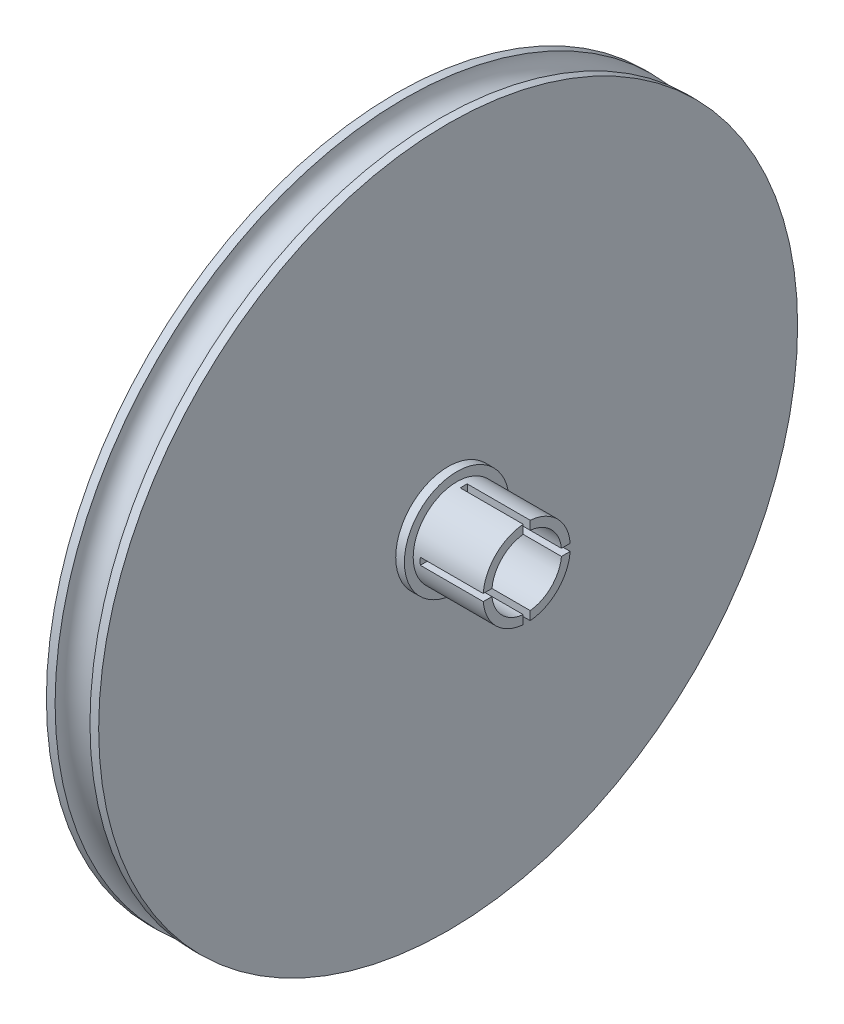
SolidWorks part; units mm, degrees
ref_plane "Front Plane" through (0, 0, 0) normal (0, 0, 1) x (1, 0, 0)
ref_plane "Top Plane" through (0, 0, 0) normal (0, 1, 0) x (1, 0, 0)
ref_plane "Right Plane" through (0, 0, 0) normal (1, 0, 0) x (0, 0, -1)
sketch "Sketch1" plane through (0, 0, 0) normal (0, 0, 1) x (1, 0, 0)
  line L0 (0, 0) -> (9.4996, 0) construction
  line L1 (0, 31.75) -> (0.7916, 31.75)
  line L2 (0, 31.75) -> (0, 3.1725)
  line L3 (0, 3.1725) -> (11.8872, 3.1725)
  line L4 (4.7498, 31.75) -> (4.7498, 4.7625)
  line L5 (3.9582, 31.75) -> (4.7498, 31.75)
  line L6 (0.7916, 31.75) -> (3.9582, 31.75) construction
  line L7 (0, 31.75) -> (4.7498, 31.75) construction
  line L8 (4.7498, 4.7625) -> (11.8872, 4.7625)
  line L9 (11.8872, 4.7625) -> (11.8872, 3.1725)
  circle A0 centre (2.3749, 31.75) radius 1.5833 construction
  arc A1 (0.7916, 31.75) -> (3.9582, 31.75) centre (2.3749, 31.75) ccw
  dimension "D2" = 3.1667
  dimension "Inside Diameter [A]" = 6.3449
  dimension "Outside Diameter [OD]" = 63.5
  dimension "D1" = 4.7498
  dimension "Diameter [E]" = 9.525
  dimension "D3" = 11.8872
revolve "Revolve1-MAIN BODY" add sketch "Sketch1" angle 360 about L0
sketch "Sketch2" plane through (0, 0, 0) normal (0, 0, 1) x (1, 0, 0)
  line L0 (0, 0) -> (10.084, 0) construction
  line L1 (0, 0) -> (9.4996, 0) construction
  line L2 (11.8872, 4.7625) -> (4.7498, 4.7625) construction
  line L3 (5.5372, 4.7625) -> (11.8872, 4.7625)
  line L4 (5.5372, 4.7625) -> (5.5372, 3.9624)
  line L5 (5.5372, 3.9624) -> (11.8872, 3.9624)
  line L6 (11.8872, 4.7625) -> (11.8872, 3.9624)
  line L7 (11.8872, -4.7625) -> (11.8872, 4.7625) construction
  dimension "D1" = 6.35
  dimension "Diameter [D]" = 7.9248
revolve "Cut-Revolve1-SLOT" cut sketch "Sketch2" angle 360 about L0
sketch "Sketch3" plane through (11.8872, 0, 0) normal (1, 0, 0) x (0, 0, -1)
  line L0 (0, 0) -> (0, 3.9624) construction
  line L1 (-0.3175, 3.9497) -> (-0.3175, 3.1565)
  line L2 (0.3175, 3.9497) -> (0.3175, 3.1565)
  circle A0 centre (0, 0) radius 3.1725 construction
  circle A1 centre (0, 0) radius 3.9624
  arc A2 (0.3175, 3.9497) -> (-0.3175, 3.9497) centre (0, 0) ccw
  arc A3 (0.3175, 3.1565) -> (-0.3175, 3.1565) centre (0, 0) ccw
  dimension "D2" = 0.635
  dimension "D1" = 0
extrude "Cut-Extrude1-SLOT" cut sketch "Sketch3" against normal blind 5.715
pattern_circular "CirPattern1" count 4 over 360 about axis through (0, 0, 0) along (1, 0, 0) of "Cut-Extrude1-SLOT"
equation "\"D2@Sketch1\"=\"D1@Sketch1\"*.6667"
equation "\"D1@Cut-Extrude1-SLOT\" = \"D1@Sketch2\"*.9"
